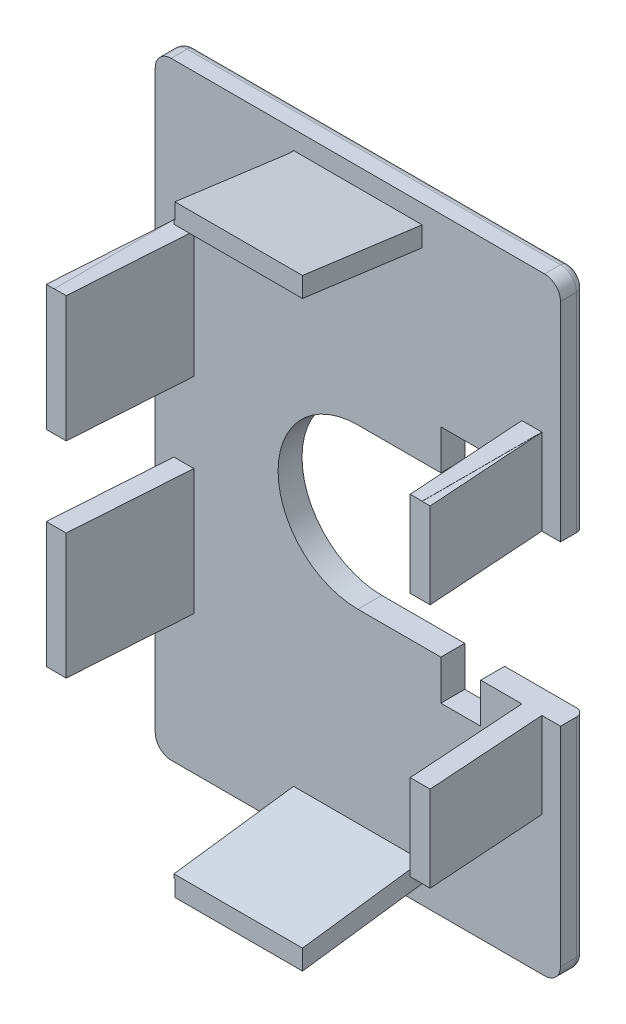
SolidWorks part; units mm, degrees
material "PLA"
ref_plane "Alzado" through (0, 0, 0) normal (0, 0, 1) x (1, 0, 0)
ref_plane "Planta" through (0, 0, 0) normal (0, 1, 0) x (1, 0, 0)
ref_plane "Vista lateral" through (0, 0, 0) normal (1, 0, 0) x (0, 0, -1)
sketch "Croquis1" plane through (0, 0, 0) normal (0, 0, 1) x (1, 0, 0)
  line L1 (25.4, 38.1) -> (-25.4, 38.1)
  line L2 (25.4, 38.1) -> (25.4, -38.1)
  line L3 (25.4, -38.1) -> (-25.4, -38.1)
  line L4 (-25.4, 38.1) -> (-25.4, -38.1)
  line L5 (25.4, 38.1) -> (-25.4, -38.1) construction
  line L6 (25.4, -38.1) -> (-25.4, 38.1) construction
  point P0 (0, 0)
  dimension "D1" = 76.2
  dimension "D2" = 50.8
extrude "Saliente-Extruir1" add sketch "Croquis1" along normal blind 18
sketch "Croquis2" plane through (0, 0, 18) normal (0, 0, 1) x (1, 0, 0)
  line L0 (25.4, 38.1) -> (-25.4, 38.1) construction
  line L1 (-23.06, 35.76) -> (23.06, 35.76)
  line L2 (-23.06, 35.76) -> (-23.06, -35.76)
  line L3 (-23.06, -35.76) -> (23.06, -35.76)
  line L4 (23.06, 35.76) -> (23.06, -35.76)
  line L5 (-25.4, -38.1) -> (25.4, -38.1) construction
  line L6 (-25.4, 38.1) -> (-25.4, -38.1) construction
  line L7 (25.4, -38.1) -> (25.4, 38.1) construction
  line L9 (-25.4, 38.1) -> (25.4, 38.1)
  line L10 (-25.4, 38.1) -> (-25.4, -38.1)
  line L11 (-25.4, -38.1) -> (25.4, -38.1)
  line L12 (25.4, 38.1) -> (25.4, -38.1)
  line L13 (-19.4, 32.1) -> (19.4, 32.1)
  line L14 (-19.4, 32.1) -> (-19.4, -32.1)
  line L15 (-19.4, -32.1) -> (19.4, -32.1)
  line L16 (19.4, 32.1) -> (19.4, -32.1)
  line M9 (-25.4, 38.1) -> (-25.4, -38.1)
  line M10 (-25.4, -38.1) -> (25.4, -38.1)
  line M11 (25.4, -38.1) -> (25.4, 38.1)
  line M12 (25.4, 38.1) -> (-25.4, 38.1)
  dimension "D1" = 2.34
  dimension "D2" = 2.34
  dimension "D3" = 2.34
  dimension "D4" = 2.34
  dimension "D5" = 6
  dimension "D6" = 6
  dimension "D7" = 6
  dimension "D8" = 6
extrude "Cortar-Extruir1" cut sketch "Croquis2" against normal blind 15 contours L1 L4 L3 L2 M12 M9 M10 M11 | L16 L13 L14 L15
sketch "Croquis3" plane through (0, 0, 18) normal (0, 0, 1) x (1, 0, 0)
  line L0 (-23.06, 35.76) -> (-23.06, -35.76) construction
  line L1 (-23.06, 22.1) -> (-19.4, 22.1)
  line L2 (-23.06, 22.1) -> (-23.06, -22.1)
  line L3 (-23.06, -22.1) -> (-19.4, -22.1)
  line L4 (-19.4, 22.1) -> (-19.4, -22.1)
  line L5 (-19.4, 32.1) -> (-19.4, -32.1) construction
  line L6 (-19.4, -32.1) -> (19.4, -32.1) construction
  line L7 (-9.4, -32.1) -> (9.3837, -32.1)
  line L8 (-9.4, -32.1) -> (-9.4, -35.76)
  line L9 (-9.4, -35.76) -> (9.3837, -35.76)
  line L10 (9.3837, -32.1) -> (9.3837, -35.76)
  line L11 (-23.06, -35.76) -> (23.06, -35.76) construction
  line L12 (19.4, 32.1) -> (19.4, -32.1) construction
  line L13 (19.4, -22.1) -> (23.06, -22.1)
  line L14 (19.4, -22.1) -> (19.4, 22.1)
  line L15 (19.4, 22.1) -> (23.06, 22.1)
  line L16 (23.06, -22.1) -> (23.06, 22.1)
  line L17 (23.06, 35.76) -> (23.06, -35.76) construction
  line L18 (-23.06, 35.76) -> (23.06, 35.76) construction
  line L19 (-9.4, 35.76) -> (9.4, 35.76)
  line L20 (-9.4, 35.76) -> (-9.4, 32.1)
  line L21 (-9.4, 32.1) -> (9.4, 32.1)
  line L22 (9.4, 35.76) -> (9.4, 32.1)
  line L23 (-19.4, 32.1) -> (19.4, 32.1) construction
  line L24 (-19.4, 32.1) -> (-19.4, -32.1) construction
  line L25 (19.4, 32.1) -> (19.4, -32.1) construction
  dimension "D1" = 10
  dimension "D2" = 10
  dimension "D3" = 10
  dimension "D4" = 10
  dimension "D5" = 10
  dimension "D6" = 10
  dimension "D7" = 10
extrude "Cortar-Extruir2" [suppressed] cut sketch "Croquis3" against normal blind 7
fillet "Redondeo1" [suppressed] radius 2
fillet "Redondeo2" [suppressed] radius 1
sketch "Croquis5" [suppressed] plane through (0, -38.1, 0) normal (0, -1, 0) x (1, 0, 0)
  line L0 (-23.4, 3) -> (23.4, 3) construction
  line L1 (-3, 3) -> (3, 3)
  line L2 (-3, 3) -> (-3, 1.5)
  line L3 (-3, 1.5) -> (3, 1.5)
  line L4 (3, 3) -> (3, 1.5)
  line L5 (0, 1) -> (0, 3) construction
  line L6 (-23.4, 1) -> (23.4, 1) construction
  dimension "D1" = 3
  dimension "D2" = 3
  dimension "D3" = 1.5
extrude "Cortar-Extruir4" [suppressed] cut sketch "Croquis5" against normal blind 6
sketch "Croquis6" plane through (0, 0, 18) normal (0, 0, 1) x (1, 0, 0)
  line L0 (-23.06, 35.76) -> (-8.06, 35.76)
  line L1 (-23.06, 35.76) -> (23.06, 35.76) construction
  line L2 (-8.06, 35.76) -> (-8.06, 32.1)
  line L3 (-19.4, 32.1) -> (19.4, 32.1) construction
  line L4 (-8.06, 32.1) -> (-19.4, 32.1)
  line L5 (-19.4, 32.1) -> (-19.4, 20.76)
  line L6 (-19.4, 32.1) -> (-19.4, -32.1) construction
  line L7 (-19.4, 20.76) -> (-23.06, 20.76)
  line L8 (-23.06, 35.76) -> (-23.06, -35.76) construction
  line L9 (-23.06, 20.76) -> (-23.06, 35.76)
  line L10 (23.06, 35.76) -> (8.06, 35.76)
  line L11 (-23.06, 35.76) -> (23.06, 35.76) construction
  line L12 (8.06, 35.76) -> (8.06, 32.1)
  line L13 (8.06, 32.1) -> (19.4, 32.1)
  line L14 (19.4, 32.1) -> (19.4, -32.1) construction
  line L15 (19.4, 32.1) -> (19.4, -32.1) construction
  line L16 (19.4, 32.1) -> (19.4, 20.76)
  line L17 (19.4, 20.76) -> (23.06, 20.76)
  line L18 (23.06, 35.76) -> (23.06, -35.76) construction
  line L19 (23.06, 20.76) -> (23.06, 35.76)
  line L20 (-23.06, -35.76) -> (-23.06, -20.76)
  line L21 (-23.06, 35.76) -> (-23.06, -35.76) construction
  line L22 (-23.06, -20.76) -> (-19.4, -20.76)
  line L23 (-19.4, 32.1) -> (-19.4, -32.1) construction
  line L24 (-19.4, -20.76) -> (-19.4, -32.1)
  line L25 (-19.4, -32.1) -> (-8.06, -32.1)
  line L26 (-19.4, -32.1) -> (19.4, -32.1) construction
  line L27 (-8.06, -32.1) -> (-8.06, -35.76)
  line L28 (-23.06, -35.76) -> (23.06, -35.76) construction
  line L29 (-8.06, -35.76) -> (-23.06, -35.76)
  line L30 (23.06, -35.76) -> (8.06, -35.76)
  line L31 (-23.06, -35.76) -> (23.06, -35.76) construction
  line L32 (8.06, -35.76) -> (8.06, -32.1)
  line L33 (-19.4, -32.1) -> (19.4, -32.1) construction
  line L34 (8.06, -32.1) -> (19.4, -32.1)
  line L35 (19.4, -32.1) -> (19.4, -20.76)
  line L36 (19.4, -20.76) -> (23.06, -20.76)
  line L37 (23.06, 35.76) -> (23.06, -35.76) construction
  line L38 (23.06, -20.76) -> (23.06, -35.76)
  dimension "D1" = 15
  dimension "D2" = 15
  dimension "D3" = 15
  dimension "D4" = 15
  dimension "D5" = 15
  dimension "D6" = 15
  dimension "D7" = 15
  dimension "D8" = 15
extrude "Cortar-Extruir8" cut sketch "Croquis6" against normal blind 15
sketch "Croquis10" plane through (0, -20.76, 0) normal (0, -1, 0) x (-1, 0, 0)
  line L0 (23.06, -18) -> (24.06, -18)
  line L1 (24.06, -18) -> (23.06, -3)
  line L2 (23.06, -3) -> (23.06, -18)
  line L3 (-23.06, -18) -> (-24.06, -18)
  line L4 (-24.06, -18) -> (-23.06, -3)
  line L5 (-23.06, -3) -> (-23.06, -18)
  dimension "D1" = 1
  dimension "D2" = 1
extrude "Saliente-Extruir3" add sketch "Croquis10" against normal blind 41.5
sketch "Croquis11" plane through (0, -20.76, 0) normal (0, -1, 0) x (1, 0, 0)
  line L0 (-19.4, 18) -> (-21.56, 18)
  line L1 (-19.4, 18) -> (-24.06, 18) construction
  line L2 (-21.56, 18) -> (-20.56, 3)
  line L3 (-19.4, 3) -> (-23.06, 3) construction
  line L4 (-20.56, 3) -> (-19.4, 3)
  line L5 (-19.4, 18) -> (-19.4, 3)
  dimension "D1" = 2.5
  dimension "D2" = 1.16
extrude "Cortar-Extruir9" cut sketch "Croquis11" against normal blind 51.5
sketch "Croquis12" plane through (0, -20.76, 0) normal (0, -1, 0) x (1, 0, 0)
  line L0 (19.4, 18) -> (19.4, 3)
  line L1 (19.4, 3) -> (20.56, 3)
  line L2 (23.06, 3) -> (19.4, 3) construction
  line L3 (20.56, 3) -> (21.56, 18)
  line L4 (24.06, 18) -> (19.4, 18) construction
  line L5 (21.56, 18) -> (19.4, 18)
  dimension "D1" = 2.5
  dimension "D2" = 1.16
extrude "Cortar-Extruir10" cut sketch "Croquis12" against normal blind 51.5
sketch "Croquis13" plane through (8.06, 0, 0) normal (1, 0, 0) x (0, 0, -1)
  line L0 (-18, -35.76) -> (-18, -37.76)
  line L1 (-18, -37.76) -> (-3, -35.76)
  line L2 (-3, -35.76) -> (-18, -35.76)
  line L3 (-18, 35.76) -> (-18, 37.76)
  line L4 (-18, 37.76) -> (-3, 35.76)
  line L5 (-3, 35.76) -> (-18, 35.76)
  dimension "D1" = 2
  dimension "D2" = 2
extrude "Saliente-Extruir4" add sketch "Croquis13" against normal blind 16
sketch "Croquis14" plane through (8.06, 0, 0) normal (1, 0, 0) x (0, 0, -1)
  line L0 (-3, -32.1) -> (-18, -32.1)
  line L1 (-18, -32.1) -> (-18, -35.26)
  line L2 (-18, -32.1) -> (-18, -37.76) construction
  line L3 (-18, -35.26) -> (-3, -33.26)
  line L4 (-3, -32.1) -> (-3, -35.76) construction
  line L5 (-3, -33.26) -> (-3, -32.1)
  line L6 (-18, 32.1) -> (-18, 35.26)
  line L7 (-18, 37.76) -> (-18, 32.1) construction
  line L8 (-18, 35.26) -> (-3, 33.26)
  line L9 (-3, 35.76) -> (-3, 32.1) construction
  line L10 (-3, 33.26) -> (-3, 32.1)
  line L11 (-3, 32.1) -> (-18, 32.1)
  dimension "D1" = 2.5
  dimension "D2" = 1.16
  dimension "D3" = 2.5
  dimension "D4" = 1.16
extrude "Cortar-Extruir11" cut sketch "Croquis14" against normal blind 16.5
fillet "Redondeo3" radius 2 4 edges at (25.4, 38.1, 1.5) (-25.4, 38.1, 1.5) (-25.4, -38.1, 1.5) (25.4, -38.1, 1.5)
fillet "Redondeo4" radius 1 8 edges at (-24.8142, 37.5142, 0) (-25.4, 0, 0) (-24.8142, -37.5142, 0) (0, -38.1, 0) (24.8142, -37.5142, 0) (25.4, 0, 0) (24.8142, 37.5142, 0) (0, 38.1, 0)
sketch "Croquis15" plane through (0, 0, 18) normal (0, 0, 1) x (1, 0, 0)
  line L0 (-24.06, -0.01) -> (24.06, -0.01) construction
  line L1 (-24.06, 20.74) -> (-24.06, -20.76) construction
  line L2 (24.06, 20.74) -> (24.06, -20.76) construction
  line L4 (-24.06, 4.99) -> (24.06, 4.99)
  line L5 (-24.06, 4.99) -> (-24.06, -5.01)
  line L6 (-24.06, -5.01) -> (24.06, -5.01)
  line L7 (24.06, 4.99) -> (24.06, -5.01)
  dimension "D1" = 5
  dimension "D2" = 5
extrude "Cortar-Extruir12" cut sketch "Croquis15" against normal blind 15
sketch "Croquis16" plane through (0, -38.1, 0) normal (0, -1, 0) x (1, 0, 0)
  line L0 (-23.4, 3) -> (23.4, 3) construction
  line L1 (-4, 3) -> (4, 3)
  line L2 (-4, 3) -> (-4, 1.5)
  line L3 (-4, 1.5) -> (4, 1.5)
  line L4 (4, 3) -> (4, 1.5)
  dimension "D1" = 1.5
  dimension "D2" = 8
  dimension "D3" = 4
extrude "Cortar-Extruir13" cut sketch "Croquis16" against normal blind 2
sketch "Croquis17" plane through (0, 0, 3) normal (0, 0, 1) x (1, 0, 0)
  line L0 (-25.4, 36.1) -> (-25.4, -36.1) construction
  line L1 (-23.4, -38.1) -> (-4, -38.1) construction
  circle A0 centre (-13.4, -23.1) radius 3
  dimension "D2" = 6
  dimension "D1" = 12
  dimension "D3" = 15
extrude "Cortar-Extruir14" [suppressed] cut sketch "Croquis17" against normal blind 10
sketch "Croquis18" plane through (0, 0, 3) normal (0, 0, 1) x (1, 0, 0)
  line L0 (0, 10) -> (25.4, 10)
  line L1 (25.4, -36.1) -> (25.4, 36.1) construction
  line L2 (0, -10) -> (25.4, -10)
  line L3 (25.4, -10) -> (25.4, 10)
  circle A0 centre (0, 0) radius 10
  line M7 (25.4, -36.1) -> (25.4, 36.1)
  line M14 (23.06, 20.74) -> (23.06, 4.99)
  line M15 (23.06, 4.99) -> (20.56, 4.99)
  line M16 (20.56, 4.99) -> (20.56, 20.76)
  line M28 (20.56, -20.76) -> (20.56, -5.01)
  line M29 (20.56, -5.01) -> (23.06, -5.01)
  line M30 (23.06, -5.01) -> (23.06, -20.76)
  dimension "D1" = 20
extrude "Cortar-Extruir16" cut sketch "Croquis18" against normal through all and the other way through all contours A0 | L2 M28 M30 M29 | L0 M16 M15 M14 | A0 L2 L0 M28 M29 M30 M7 M14 M15 M16
sketch "Croquis19" plane through (0, 0, 3) normal (0, 0, 1) x (1, 0, 0)
  line L0 (0, 10) -> (20.56, 10) construction
  line L1 (10.4, 10) -> (15.4, 10)
  line L2 (10.4, 10) -> (10.4, 15)
  line L3 (10.4, 15) -> (15.4, 15)
  line L4 (15.4, 10) -> (15.4, 15)
  line L5 (0, -10) -> (20.56, -10) construction
  line L6 (10.4, -10) -> (15.4, -10)
  line L7 (10.4, -10) -> (10.4, -15)
  line L8 (10.4, -15) -> (15.4, -15)
  line L9 (15.4, -10) -> (15.4, -15)
  dimension "D1" = 5
  dimension "D2" = 5
  dimension "D3" = 5
  dimension "D4" = 5
  dimension "D5" = 10
  dimension "D6" = 10
extrude "Cortar-Extruir17" cut sketch "Croquis19" against normal through all
